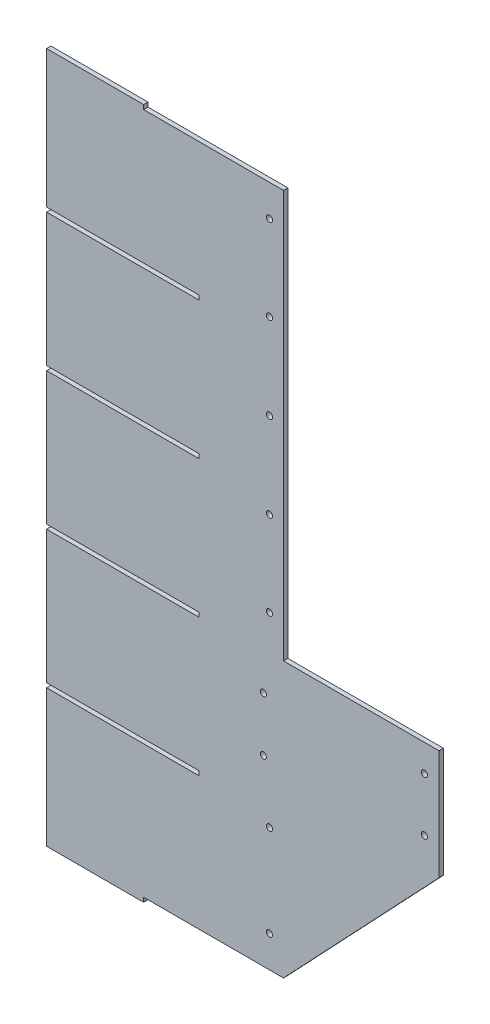
SolidWorks part; units mm, degrees
material "6061-T6 (SS)"
ref_plane "X-Y Datum" through (0, 0, 0) normal (0, 0, 1) x (1, 0, 0)
ref_plane "X-Z Datum" through (0, 0, 0) normal (0, 1, 0) x (1, 0, 0)
ref_plane "Y-Z Datum" through (0, 0, 0) normal (1, 0, 0) x (0, 0, -1)
sketch "Sketch1" plane through (0, 0, 0) normal (0, 0, 1) x (1, 0, 0)
  line L1 (129.0131, 254.2454) -> (-18.6854, 254.2454)
  line L3 (129.0131, -241.3467) -> (-18.6854, -241.3467)
  line L4 (-18.6854, 254.2454) -> (-18.6854, 157.667)
  line L24 (129.0131, 254.2454) -> (129.0131, -241.3467)
  line L25 (92.0885, 157.667) -> (-18.6854, 157.667)
  line L27 (92.0885, 154.492) -> (-18.6854, 154.492)
  line L29 (92.0885, 57.9136) -> (-18.6854, 57.9136)
  line L31 (92.0885, 54.7386) -> (-18.6854, 54.7386)
  line L33 (92.0885, -41.8399) -> (-18.6854, -41.8399)
  line L35 (92.0885, -45.0149) -> (-18.6854, -45.0149)
  line L37 (92.0885, -141.5933) -> (-18.6854, -141.5933)
  line L39 (92.0885, -144.7683) -> (-18.6854, -144.7683)
  line L41 (92.0885, -141.5933) -> (92.0885, -144.7683)
  line L42 (92.0885, -41.8399) -> (92.0885, -45.0149)
  line L43 (92.0885, 57.9136) -> (92.0885, 54.7386)
  line L44 (-18.6854, -144.7683) -> (-18.6854, -241.3467)
  line L45 (-18.6854, -45.0149) -> (-18.6854, -141.5933)
  line L46 (-18.6854, 54.7386) -> (-18.6854, -41.8399)
  line L47 (-18.6854, 154.492) -> (-18.6854, 57.9136)
  line L48 (92.0885, 157.667) -> (92.0885, 154.492)
extrude "Boss-Extrude2" add sketch "Sketch1" along normal blind 3.175
sketch "Sketch2" plane through (0, 0, 3.175) normal (0, 0, 1) x (1, 0, 0)
  line L0 (129.0131, -241.3467) -> (153.4072, -227.2627) construction
  line L2 (129.0131, 254.2454) -> (129.0131, -241.3467)
  line L15 (153.4072, -227.2627) -> (153.4072, -187.8927)
  line L18 (153.4072, -143.1808) -> (153.4072, 240.1614)
  line L19 (153.4072, 240.1614) -> (153.4072, 254.2454)
  line L21 (153.4072, -187.8927) -> (153.4072, -143.1808)
  line L22 (153.4072, 254.2454) -> (129.0131, 254.2454)
  line L23 (129.0131, -241.3467) -> (153.4072, -241.3467)
  line L24 (153.4072, -241.3467) -> (153.4072, -227.2627)
extrude "Boss-Extrude3" add sketch "Sketch2" against normal through all
sketch "Sketch3" plane through (0, 0, 3.175) normal (0, 0, 1) x (1, 0, 0)
  line L8 (153.4072, 6.4494) -> (-81.8872, 6.4494) construction
  line L9 (51.8072, 257.4204) -> (51.8072, 254.2454)
  line L18 (153.4072, 257.4204) -> (51.8072, 257.4204)
  line L19 (153.4072, 257.4204) -> (153.4072, 270.1204)
  line L20 (153.4072, 270.1204) -> (30.4963, 270.1204)
  line L21 (30.4963, 270.1204) -> (6.7146, 286.3764)
  line L22 (-18.6854, 286.3764) -> (6.7146, 286.3764)
  line L23 (-18.6854, 254.2454) -> (-18.6854, 286.3764)
  line L24 (51.8072, 254.2454) -> (-18.6854, 254.2454)
extrude "Boss-Extrude4" [suppressed] add sketch "Sketch3" against normal through all
sketch "Sketch4" [suppressed] plane through (0, 0, 3.175) normal (0, 0, 1) x (1, 0, 0)
  line L1 (153.4072, 270.1204) -> (221.7231, 270.1204)
  line L2 (153.4072, 270.1204) -> (153.4072, 257.4204)
  line L3 (153.4072, 257.4204) -> (221.7231, 257.4204)
  line L4 (221.7231, 270.1204) -> (221.7231, 257.4204)
  line L5 (153.4072, 254.2454) -> (221.7231, 254.2454)
  line L6 (153.4072, 254.2454) -> (153.4072, 157.667)
  line L7 (153.4072, 157.667) -> (221.7231, 157.667)
  line L8 (221.7231, 254.2454) -> (221.7231, 157.667)
  dimension "D1" = 68.3158
extrude "Boss-Extrude5" [suppressed] add sketch "Sketch4" against normal through all
sketch "Sketch7" plane through (0, 0, 3.175) normal (0, 0, 1) x (1, 0, 0)
  line L0 (92.0885, -41.8399) -> (153.4072, -41.8399) construction
  line L1 (153.2294, -121.7811) -> (153.4072, -41.8399)
  line L2 (153.4072, -241.3467) -> (153.4072, 254.2454) construction
  line L3 (153.4072, -41.8399) -> (266.4372, -41.8399)
  line L4 (266.4372, -41.8399) -> (266.4372, -121.7811)
  line L6 (153.4072, -241.3467) -> (153.4072, 254.2454) construction
  line L7 (266.4372, -121.7811) -> (153.4072, -241.3467)
  line L8 (153.4072, -241.3467) -> (153.2294, -121.7811)
extrude "Boss-Extrude6" add sketch "Sketch7" against normal through all
sketch "Sketch8" plane through (0, 0, 3.175) normal (0, 0, 1) x (1, 0, 0)
  line L1 (-18.6854, 254.2454) -> (51.8072, 254.2454)
  line L2 (-18.6854, 254.2454) -> (-18.6854, 257.4204)
  line L3 (-18.6854, 257.4204) -> (51.8072, 257.4204)
  line L4 (51.8072, 254.2454) -> (51.8072, 257.4204)
  line L5 (-18.6854, -241.3467) -> (51.8072, -241.3467)
  line L6 (-18.6854, -241.3467) -> (-18.6854, -244.5217)
  line L7 (-18.6854, -244.5217) -> (51.8072, -244.5217)
  line L8 (51.8072, -241.3467) -> (51.8072, -244.5217)
extrude "Boss-Extrude7" add sketch "Sketch8" against normal through all
sketch "Sketch12" plane through (0, 0, 3.175) normal (0, 0, 1) x (1, 0, 0)
  line L0 (-18.6854, 257.4204) -> (289.5814, 257.4204) construction
  line L1 (-18.6854, 257.4204) -> (-18.6854, -144.2662) construction
  line L2 (-18.6854, -144.2662) -> (289.5814, -144.2662) construction
  line L3 (289.5814, 257.4204) -> (289.5814, -144.2662) construction
  point P0 (143.2472, 244.0133)
  point P1 (143.2472, 171.1213)
  point P2 (143.2472, 98.2292)
  point P3 (143.2472, 25.3372)
  point P4 (143.2472, -47.5549)
  point P5 (170.6792, -74.9869)
  point P6 (210.7117, -74.9869)
  point P7 (250.7441, -74.9869)
  point P8 (256.2772, -80.52)
  point P9 (256.2772, -106.7475)
  point P10 (256.2772, -132.9751)
  point P15 (143.2472, -160.6738)
  point P16 (143.2472, -195.8942)
  point P17 (143.2472, -231.1146)
sketch "Sketch14" plane through (0, 0, 0) normal (0, 0, -1) x (-1, 0, 0)
  line L0 (18.6854, -244.5217) -> (-23.3644, -244.5217) construction
  line L1 (18.6854, -244.5217) -> (18.6854, -226.8054) construction
  line L2 (18.6854, -226.8054) -> (-23.3644, -226.8054) construction
  line L3 (-23.3644, -244.5217) -> (-23.3644, -226.8054) construction
  line L4 (-258.5632, -117.2684) -> (-255.7997, -117.2684) construction
  line L5 (-255.7997, -117.2684) -> (-255.7997, -100.4453) construction
  circle A0 centre (-143.2472, -218.4146) radius 2.25
  circle A1 centre (-143.2472, -151.7533) radius 2.25
  circle A2 centre (-255.7997, -100.4453) radius 2.25
  circle A3 centre (-255.7997, -61.597) radius 2.25
  circle A4 centre (-143.2472, -16.4399) radius 2.25
  circle A5 centre (-143.2472, 45.2329) radius 2.25
  circle A6 centre (-143.2472, 107.4367) radius 2.25
  circle A7 centre (-143.2472, 169.6405) radius 2.25
  circle A8 centre (-143.2472, 231.3133) radius 2.25
  point P0 (-143.2472, -218.4146)
  point P1 (-143.2472, -151.7533)
  point P2 (-255.7997, -100.4453)
  point P3 (-255.7997, -61.597)
  point P4 (-143.2472, -16.4399)
  point P5 (-143.2472, 45.2329)
  point P6 (-143.2472, 107.4367)
  point P7 (-143.2472, 169.6405)
  point P8 (-143.2472, 231.3133)
  point P13 (18.6854, -244.5217)
  point P34 (-255.7997, -61.597)
  point P36 (18.6854, -244.5217)
extrude "Cut-Extrude1" cut sketch "Sketch14" against normal through all
sketch "Sketch15" plane through (0, 0, 0) normal (0, 0, -1) x (-1, 0, 0)
  line L0 (-141.8421, -108.5523) -> (-135.7421, -108.5523) construction
  line L1 (-141.8421, -69.242) -> (-135.7421, -69.242) construction
  line L4 (-266.4372, -88.3371) -> (-206.1233, -88.3371) construction
  line L5 (-206.1233, -121.7811) -> (-206.1233, -88.3371) construction
  circle A0 centre (-138.7921, -108.5523) radius 2.25
  circle A1 centre (-138.7921, -69.242) radius 2.25
extrude "Cut-Extrude2" cut sketch "Sketch15" against normal through all
